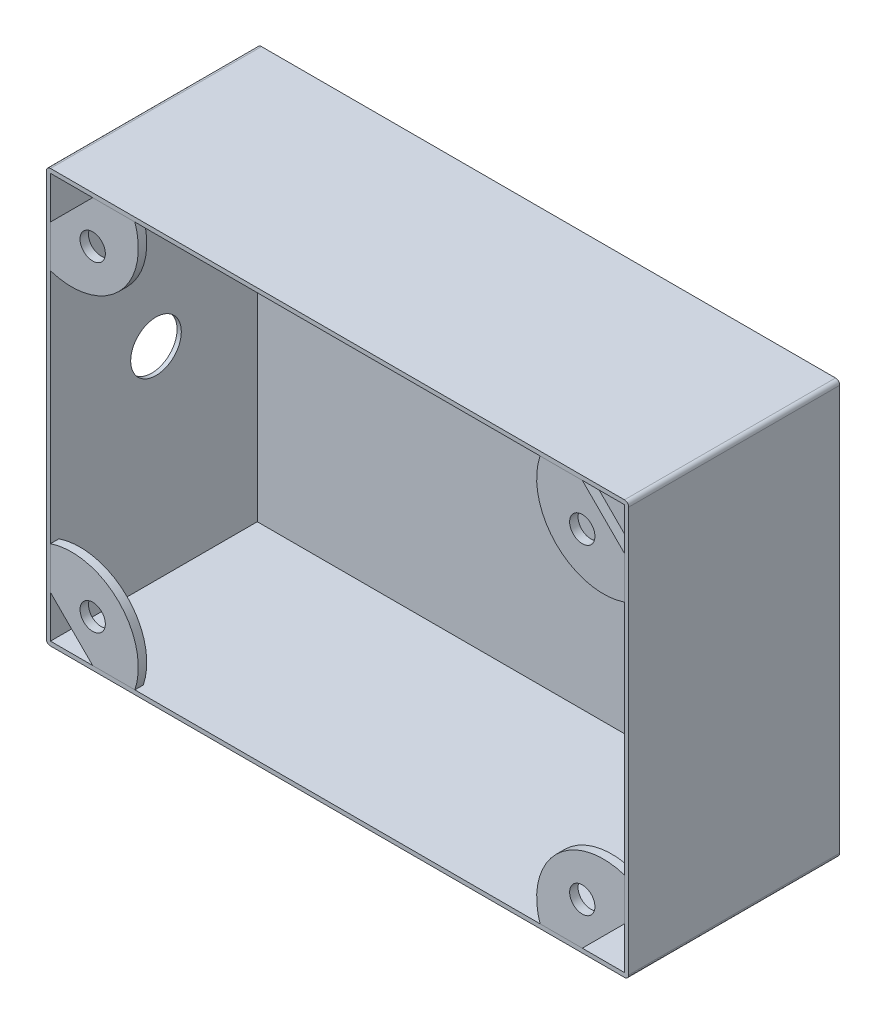
SolidWorks part; units mm, degrees
ref_plane "Alzado" through (0, 0, 0) normal (0, 0, 1) x (1, 0, 0)
ref_plane "Planta" through (0, 0, 0) normal (0, 1, 0) x (1, 0, 0)
ref_plane "Vista lateral" through (0, 0, 0) normal (1, 0, 0) x (0, 0, -1)
sketch "Croquis1" plane through (0, 0, 0) normal (0, 0, 1) x (1, 0, 0)
  line L0 (-68, 48) -> (68, 48)
  line L1 (-69, -49) -> (69, -49)
  line L2 (-69, -49) -> (-69, 49)
  line L3 (-69, 49) -> (69, 49)
  line L4 (69, -49) -> (69, 49)
  line L5 (-69, -49) -> (69, 49) construction
  line L6 (-69, 49) -> (69, -49) construction
  line L7 (68, -48) -> (68, 48)
  line L8 (-68, -48) -> (68, -48)
  line L9 (-68, -48) -> (-68, 48)
  point P0 (0, 0)
  dimension "D1" = 138
  dimension "D2" = 98
  dimension "D3" = 1
extrude "Saliente-Extruir2" add sketch "Croquis1" along normal blind 50
sketch "Croquis2" plane through (0, 0, 0) normal (0, 0, 1) x (1, 0, 0)
  line L1 (-68, -48) -> (68, -48)
  line L2 (-68, -48) -> (-68, 48)
  line L3 (-68, 48) -> (68, 48)
  line L4 (68, -48) -> (68, 48)
  line L5 (-68, -48) -> (68, 48) construction
  line L6 (-68, 48) -> (68, -48) construction
  point P0 (0, 0)
extrude "Saliente-Extruir3" add sketch "Croquis2" along normal blind 1
fillet "Redondeo1" radius 1 4 edges at (69, 49, 25) (69, -49, 25) (-69, -49, 25) (-69, 49, 25)
surface "Superficie-Plano1"
sketch "Croquis7" plane through (0, 0, 50) normal (0, 0, 1) x (1, 0, 0)
  line L1 (-68, 48) -> (-58, 38) construction
  line L47 (-68, 48) -> (-58, 48) construction
  line L56 (-68, 48) -> (-68, 38) construction
  line L68 (-68, 38) -> (-58, 38) construction
  line L69 (-58, 48) -> (-58, 38) construction
  line L70 (-68, 38) -> (-58, 48)
  line L71 (-68, 38) -> (-68, 28)
  line L72 (-68, 48) -> (-68, -48) construction
  line L73 (-58, 48) -> (-48, 48)
  line L74 (68, 48) -> (-68, 48) construction
  line L75 (0, -27.5) -> (0, 27.5) construction
  line L76 (58, 48) -> (48, 48)
  line L77 (68, 38) -> (68, 28)
  line L78 (68, 38) -> (58, 48)
  line L79 (27.5, 0) -> (-27.5, 0) construction
  line L80 (58, -48) -> (48, -48)
  line L81 (68, -38) -> (68, -28)
  line L82 (68, -38) -> (58, -48)
  line L83 (-68, -38) -> (-68, -28)
  line L84 (-68, -38) -> (-58, -48)
  line L85 (-58, -48) -> (-48, -48)
  circle A25 centre (-58, 38) radius 3
  arc A26 (-68, 28) -> (-48, 48) centre (-63, 43) ccw
  circle A27 centre (58, 38) radius 3
  arc A28 (68, 28) -> (48, 48) centre (63, 43) cw
  arc A29 (68, -28) -> (48, -48) centre (63, -43) ccw
  circle A30 centre (58, -38) radius 3
  circle A31 centre (-58, -38) radius 3
  arc A32 (-68, -28) -> (-48, -48) centre (-63, -43) cw
  point P7 (-63, 43)
  dimension "D1" = 10
extrude "Saliente-Extruir6" add sketch "Croquis7" against normal blind 2 separate body
sketch "Croquis8" plane through (-69, 0, 0) normal (-1, 0, 0) x (0, 0, 1)
  line L0 (0, 0) -> (50, 0) construction
  line L1 (50, 48) -> (50, -48) construction
  circle A0 centre (25, 0) radius 6
  dimension "D1" = 12
extrude "Cortar-Extruir1" cut sketch "Croquis8" against normal blind 2
